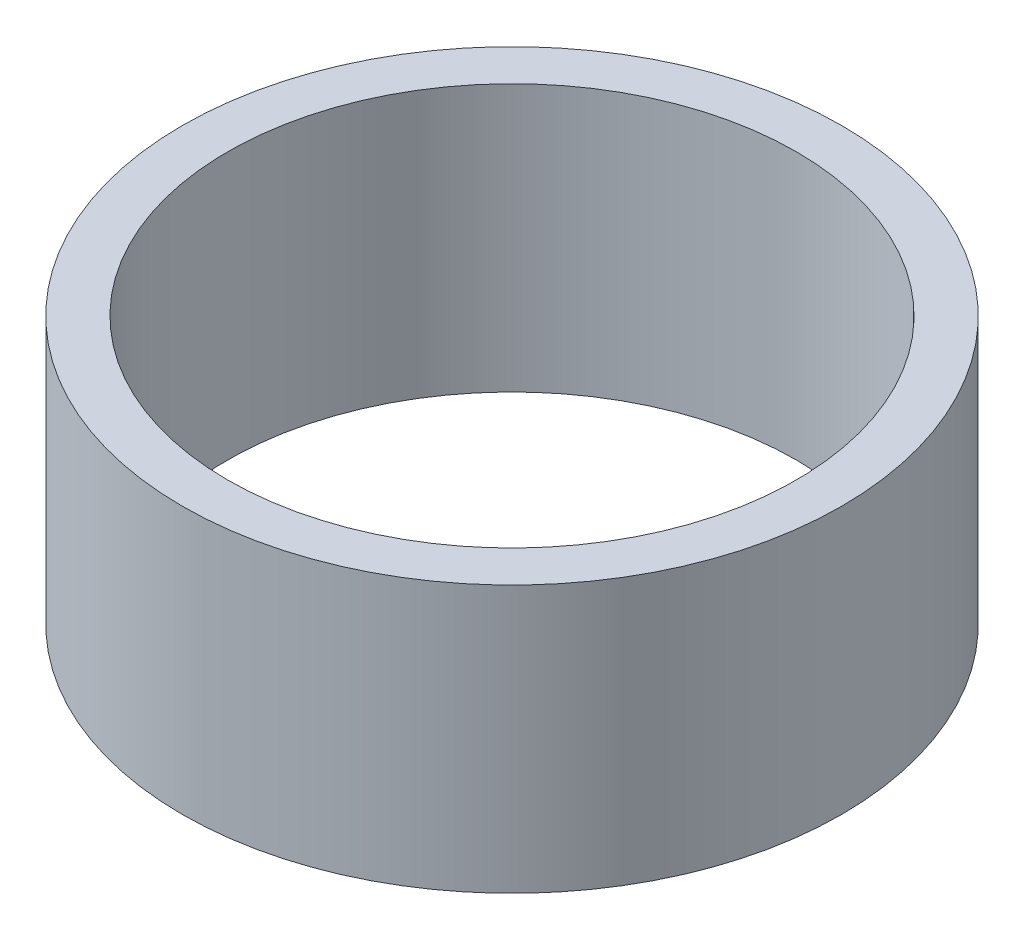
SolidWorks part; units mm, degrees
ref_plane "Front Plane" through (0, 0, 0) normal (0, 0, 1) x (1, 0, 0)
ref_plane "Top Plane" through (0, 0, 0) normal (0, 1, 0) x (1, 0, 0)
ref_plane "Right Plane" through (0, 0, 0) normal (1, 0, 0) x (0, 0, -1)
sketch "Sketch1" plane through (0, 0, 0) normal (0, 1, 0) x (1, 0, 0)
  circle A0 centre (0, 0) radius 12.35
  circle A1 centre (0, 0) radius 10.65
  dimension "D1" = 24.7
  dimension "D2" = 21.3
extrude "Boss-Extrude1" add sketch "Sketch1" along normal blind 10
